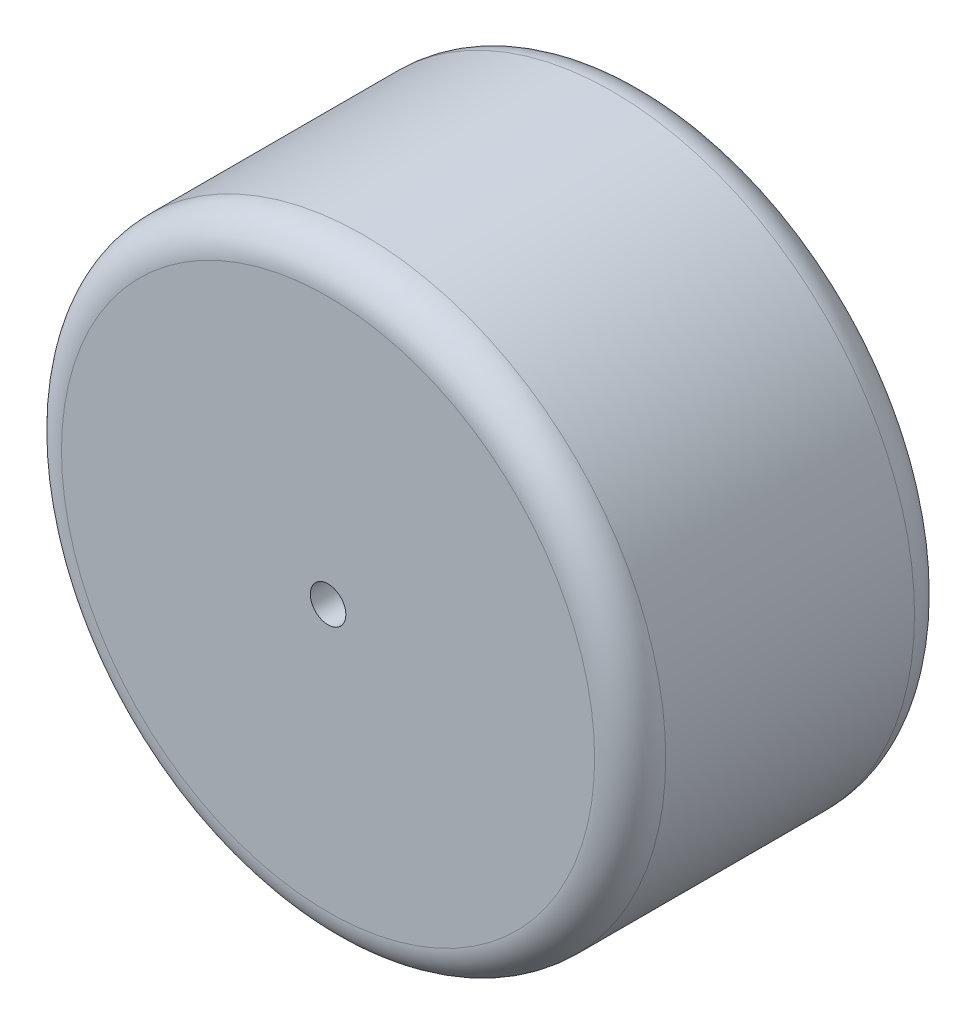
SolidWorks part; units mm, degrees
ref_plane "Front Plane" through (0, 0, 0) normal (0, 0, 1) x (1, 0, 0)
ref_plane "Top Plane" through (0, 0, 0) normal (0, 1, 0) x (1, 0, 0)
ref_plane "Right Plane" through (0, 0, 0) normal (1, 0, 0) x (0, 0, -1)
sketch "Sketch1" plane through (0, 0, 0) normal (0, 0, 1) x (1, 0, 0)
  circle A0 centre (0, 0) radius 17
  circle A1 centre (0, 0) radius 1
  dimension "D1" = 34
  dimension "D2" = 2
extrude "Boss-Extrude1" add sketch "Sketch1" along normal blind 18
fillet "Fillet1" radius 2 2 edges at (17, 0, 18) (17, 0, 0)
equation "\"ro\"= 1.35"
equation "\"rf\"= 34"
equation "\"ancho\"= 12"
equation "\"chaflan\"= 2"
